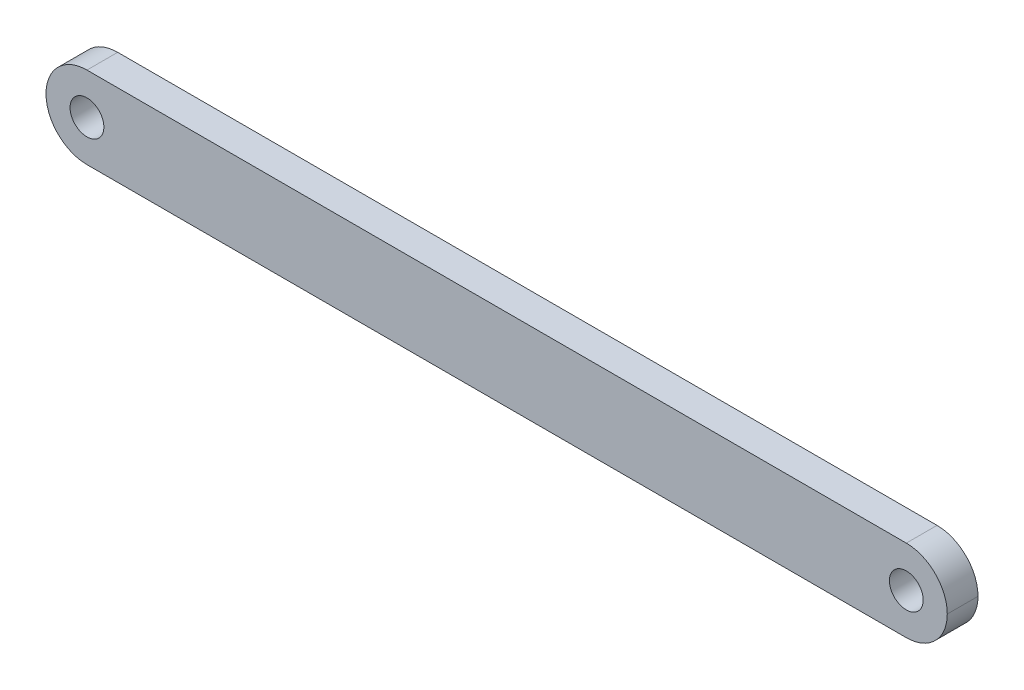
SolidWorks part; units mm, degrees
ref_plane "前视基准面" through (0, 0, 0) normal (0, 0, 1) x (1, 0, 0)
ref_plane "上视基准面" through (0, 0, 0) normal (0, 1, 0) x (1, 0, 0)
ref_plane "右视基准面" through (0, 0, 0) normal (1, 0, 0) x (0, 0, -1)
ref_plane "基准面4" through (0, 0, 0) normal (0, 0, -1) x (-1, 0, 0)
sketch "草图1" plane through (0, 0, 0) normal (0, 0, -1) x (-1, 0, 0)
  line L0 (-55.8602, 0) -> (24.1383, 0)
  line L1 (24.1383, 7.999) -> (-55.8602, 7.999)
  arc A0 (-55.8602, 7.999) -> (-59.8602, 4) centre (-55.8602, 3.999) ccw
  arc A1 (-59.8602, 4) -> (-55.8602, 0) centre (-55.8602, 4) ccw
  arc A2 (24.1383, 0) -> (28.1383, 3.999) centre (24.1383, 4) ccw
  arc A3 (28.1383, 3.999) -> (24.1383, 7.999) centre (24.1383, 3.999) ccw
  circle A4 centre (24.1388, 3.9985) radius 1.65
  circle A5 centre (-55.8597, 3.9995) radius 1.65
extrude "凸台-拉伸1" add sketch "草图1" against normal blind 3
sketch "草图2" plane through (0, 0, 0) normal (0, 0, -1) x (-1, 0, 0)
  text T0 "7"
extrude "切除-拉伸1" cut sketch "草图2" against normal blind 1
